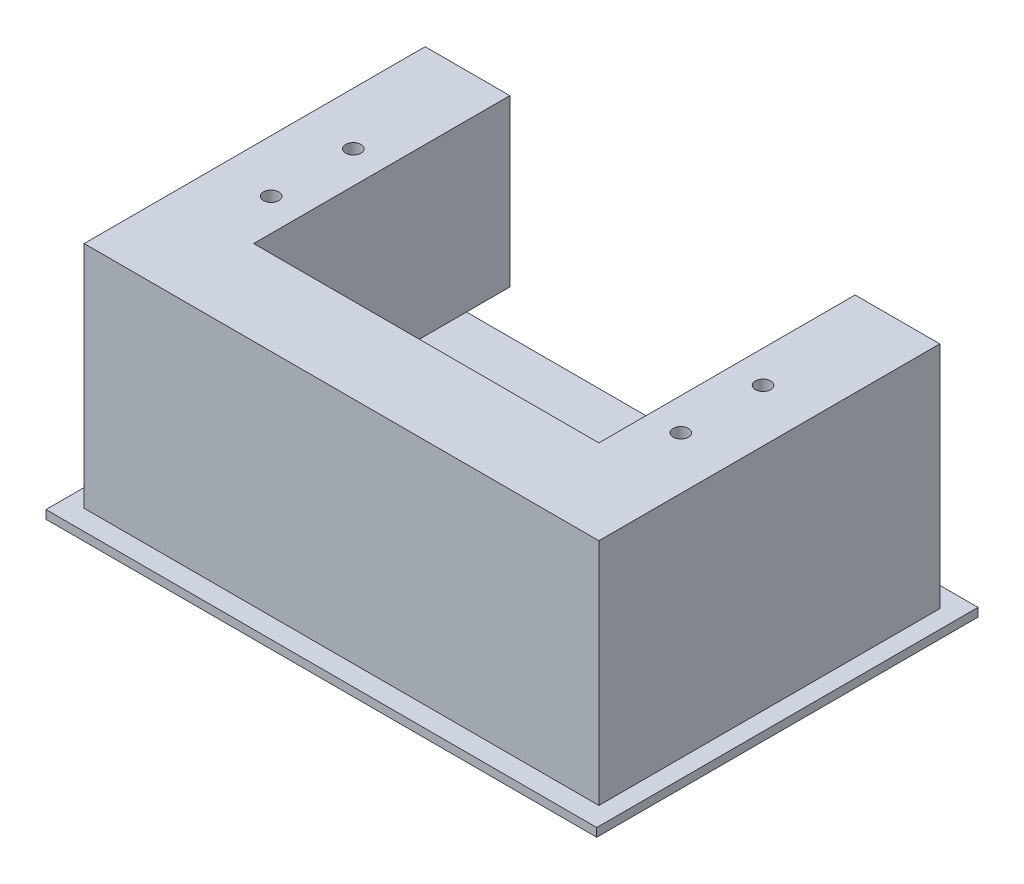
SolidWorks part; units mm, degrees
ref_plane "Front Plane" through (0, 0, 0) normal (0, 0, 1) x (1, 0, 0)
ref_plane "Top Plane" through (0, 0, 0) normal (0, 1, 0) x (1, 0, 0)
ref_plane "Right Plane" through (0, 0, 0) normal (1, 0, 0) x (0, 0, -1)
sketch "Sketch1" plane through (0, 0, 0) normal (0, 1, 0) x (1, 0, 0)
  line L1 (-32.5, -22.5) -> (32.5, -22.5)
  line L2 (-32.5, -22.5) -> (-32.5, 22.5)
  line L3 (-32.5, 22.5) -> (32.5, 22.5)
  line L4 (32.5, -22.5) -> (32.5, 22.5)
  line L5 (-32.5, -22.5) -> (32.5, 22.5) construction
  line L6 (-32.5, 22.5) -> (32.5, -22.5) construction
  point P0 (0, 0)
  dimension "D1" = 45
  dimension "D2" = 65
extrude "Boss-Extrude1" add sketch "Sketch1" along normal blind 1
sketch "Sketch2" plane through (0, 1, 0) normal (0, 1, 0) x (1, 0, 0)
  line L1 (-20.375, -20.12) -> (20.375, -20.12) construction
  line L2 (-20.375, -20.12) -> (-20.375, 20.12) construction
  line L3 (-20.375, 20.12) -> (20.375, 20.12) construction
  line L4 (20.375, -20.12) -> (20.375, 20.12) construction
  line L5 (-20.375, -20.12) -> (20.375, 20.12) construction
  line L6 (-20.375, 20.12) -> (20.375, -20.12) construction
  line L7 (20.375, 20.12) -> (30.375, 20.12)
  line L8 (20.375, 20.12) -> (20.375, -20.12)
  line L9 (20.375, -20.12) -> (30.375, -20.12)
  line L10 (30.375, 20.12) -> (30.375, -20.12)
  point P0 (0, 0)
  dimension "D1" = 40.75
  dimension "D2" = 40.24
  dimension "D3" = 10
extrude "Boss-Extrude2" add sketch "Sketch2" along normal blind 27.06 contours L8 L7 L10 L9
sketch "Sketch3" plane through (0, 28.06, 0) normal (0, 1, 0) x (1, 0, 0)
  line L0 (20.375, 0.6) -> (30.375, 0.6) construction
  line L2 (20.375, 0.6) -> (30.375, 0.6) construction
  line L3 (20.375, 20.12) -> (20.375, -20.12) construction
  circle A0 centre (24.175, 5.45) radius 0.9
  circle A1 centre (24.175, -4.25) radius 0.9
  point P2 (30.375, 1)
  dimension "D1" = 4.85
  dimension "D4" = 1.8
  dimension "D2" = 3.8
  dimension "D3" = 0.4
extrude "Cut-Extrude1" cut sketch "Sketch3" against normal blind 10 and the other way through all
mirror "Mirror3" about plane through (0, 0, 0) normal (1, 0, 0) of "Cut-Extrude1", "Boss-Extrude2"
sketch "Sketch4" plane through (-30.375, 0, 0) normal (-1, 0, 0) x (0, 0, 1)
  line L0 (-20.12, 1) -> (20.12, 1) construction
  line L1 (-4.05, 8.5) -> (4.05, 8.5)
  line L2 (-4.05, 8.5) -> (-4.05, 1)
  line L3 (-4.05, 1) -> (4.05, 1)
  line L4 (4.05, 8.5) -> (4.05, 1)
  line L5 (-4.05, 8.5) -> (4.05, 1) construction
  line L6 (-4.05, 1) -> (4.05, 8.5) construction
  line L7 (0, 0) -> (0, 10.6191) construction
  point P0 (0, 4.75)
  dimension "D1" = 8.1
  dimension "D2" = 7.5
extrude "Cut-Extrude2" cut sketch "Sketch4" against normal up to next
sketch "Sketch5" plane through (0, 1, 0) normal (0, 1, 0) x (1, 0, 0)
  line L0 (20.375, 20.12) -> (20.375, -20.12) construction
  line L1 (-20.375, 20.12) -> (20.375, 20.12)
  line L2 (-20.375, 20.12) -> (-20.375, 10.12)
  line L3 (-20.375, 10.12) -> (20.375, 10.12)
  line L4 (20.375, 20.12) -> (20.375, 10.12)
  dimension "D1" = 10
extrude "Boss-Extrude3" add sketch "Sketch5" along normal up to surface (27.06 mm away) up to face at (-24.175, 28.06, -6.35)
mirror "Mirror4" about plane through (0, 0, 0) normal (0, 0, 1) of "Boss-Extrude3"
sketch "Sketch6" plane through (-30.375, 0, 0) normal (-1, 0, 0) x (0, 0, 1)
  line L0 (-4.05, 8.5) -> (-20.12, 8.5)
  line L1 (-20.12, 28.06) -> (-20.12, 1) construction
  line L2 (-20.12, 8.5) -> (-20.12, 1)
  line L3 (-20.12, 1) -> (-4.05, 1)
  line L5 (-4.05, 8.5) -> (-4.05, 1)
extrude "Cut-Extrude3" cut sketch "Sketch6" against normal up to surface (50.75 mm away) contours L5 L3 L2 L0 up to face at (20.375, 14.53, 0)
sketch "Sketch7" plane through (0, 28.06, 0) normal (0, 1, 0) x (1, 0, 0)
  line L1 (-20.375, 10.12) -> (20.375, 10.12)
  line L2 (-20.375, 10.12) -> (-20.375, 20.12)
  line L3 (-20.375, 20.12) -> (20.375, 20.12)
  line L4 (20.375, 10.12) -> (20.375, 20.12)
extrude "Cut-Extrude4" cut sketch "Sketch7" against normal up to surface (27.06 mm away) contours L2 L1 L4 L3 up to face at (0, 1, 3.5425)
